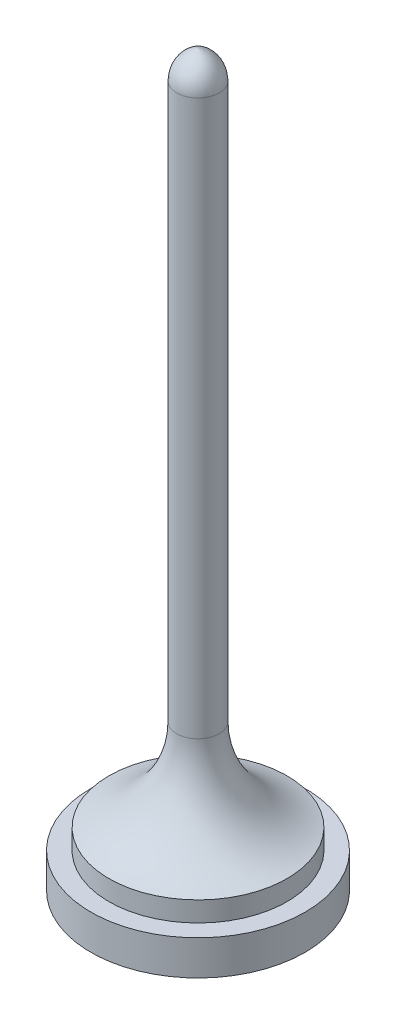
SolidWorks part; units mm, degrees
ref_plane "Front Plane" through (0, 0, 0) normal (0, 0, 1) x (1, 0, 0)
ref_plane "Top Plane" through (0, 0, 0) normal (0, 1, 0) x (1, 0, 0)
ref_plane "Right Plane" through (0, 0, 0) normal (1, 0, 0) x (0, 0, -1)
sketch "Sketch1" plane through (0, 0, 0) normal (0, 0, 1) x (1, 0, 0)
  line L0 (0, 0) -> (-16.6, 0)
  line L1 (-16.6, 0) -> (-16.6, 5.4)
  line L2 (-16.6, 5.4) -> (-13.8, 5.4)
  line L3 (-13.8, 5.4) -> (-13.8, 8.5)
  line L4 (-3.285, 22.6764) -> (-3.285, 108.6601)
  line L5 (0, 113) -> (0, 0)
  arc A0 (-13.8, 8.5) -> (-3.285, 22.6764) centre (-18.0989, 22.6764) ccw
  arc A1 (-3.285, 108.6601) -> (0, 113) centre (1.2243, 108.6601) cw
  dimension "D1" = 16.6
  dimension "D2" = 5.4
  dimension "D3" = 13.8
  dimension "D4" = 8.5
  dimension "D5" = 3.285
  dimension "D6" = 113
revolve "Revolve1" add sketch "Sketch1" angle 360 about L5
